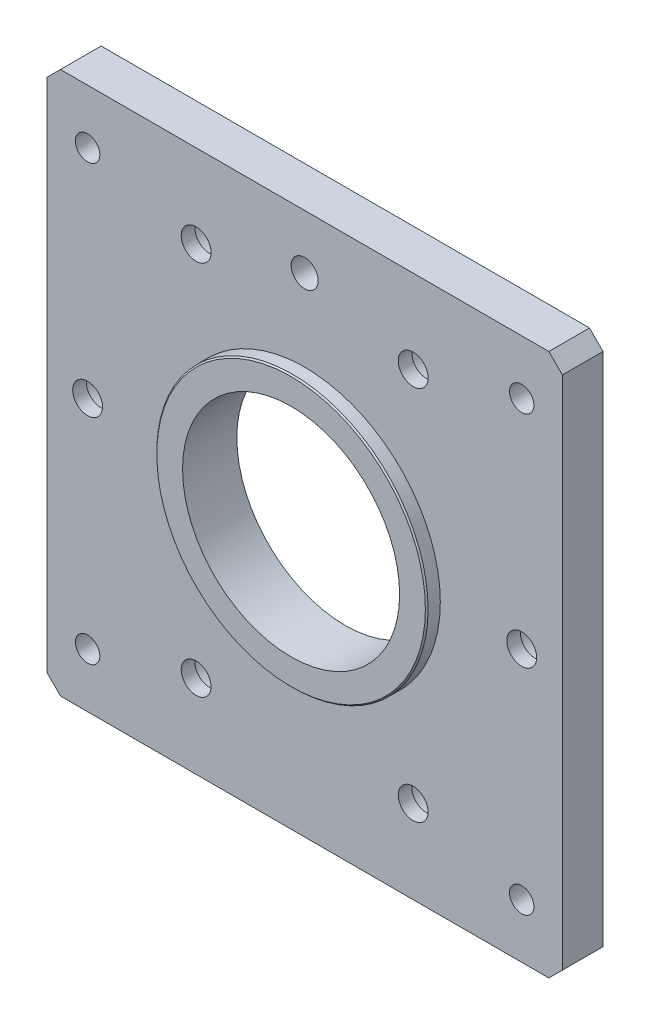
SolidWorks part; units mm, degrees
ref_plane "Alzado" through (0, 0, 0) normal (0, 0, 1) x (1, 0, 0)
ref_plane "Planta" through (0, 0, 0) normal (0, 1, 0) x (1, 0, 0)
ref_plane "Vista lateral" through (0, 0, 0) normal (1, 0, 0) x (0, 0, -1)
sketch "Croquis1" plane through (0, 0, 0) normal (0, 0, 1) x (1, 0, 0)
  line L1 (-95, 100) -> (95, 100)
  line L2 (-95, 100) -> (-95, -100)
  line L3 (-95, -100) -> (95, -100)
  line L4 (95, 100) -> (95, -100)
  line L5 (-95, 100) -> (95, -100) construction
  line L6 (-95, -100) -> (95, 100) construction
  circle A0 centre (0, 0) radius 80 construction
  circle A1 centre (80, 0) radius 5
  circle A2 centre (40, -69.282) radius 5
  circle A3 centre (-40, -69.282) radius 5
  circle A4 centre (-80, 0) radius 5
  circle A5 centre (-40, 69.282) radius 5
  circle A6 centre (40, 69.282) radius 5
  circle A7 centre (0, 80) radius 5
  circle A8 centre (0, 0) radius 40
  point P0 (0, 0)
  point P22 (0, 0)
  dimension "D1" = 160
  dimension "D4" = 10
  dimension "D6" = 10
  dimension "D7" = 80
  dimension "D2" = 190
  dimension "D3" = 200
  dimension "D5" = 6
extrude "Saliente-Extruir1" add sketch "Croquis1" along normal blind 20
sketch "Croquis2" plane through (0, 0, 20) normal (0, 0, 1) x (1, 0, 0)
  circle A0 centre (0, 0) radius 50
  dimension "D1" = 100
extrude "Cortar-Extruir1" cut sketch "Croquis2" against normal blind 5 flip side to cut
chamfer "Chaflán1" distance 0.5 angle 45 1 edges at (50, 0, 20)
chamfer "Chaflán2" distance 5 angle 45 4 edges at (95, -100, 7.5) (-95, -100, 7.5) (-95, 100, 7.5) (95, 100, 7.5)
sketch "Croquis3" plane through (0, 0, 15) normal (0, 0, 1) x (1, 0, 0)
  line L0 (-95, 95) -> (-95, -95) construction
  line L1 (-80, -80) -> (80, -80) construction
  line L2 (-80, -80) -> (-80, 80) construction
  line L3 (-80, 80) -> (80, 80) construction
  line L4 (80, -80) -> (80, 80) construction
  line L5 (-80, -80) -> (80, 80) construction
  line L6 (-80, 80) -> (80, -80) construction
  line L7 (90, 100) -> (-90, 100) construction
  circle A0 centre (-80, 80) radius 4.375
  circle A1 centre (80, 80) radius 4.375
  circle A2 centre (80, -80) radius 4.375
  circle A3 centre (-80, -80) radius 4.375
  point P0 (0, 0)
  dimension "D3" = 8.75
  dimension "D1" = 15
  dimension "D2" = 20
extrude "Cortar-Extruir2" cut sketch "Croquis3" against normal through all both and the other way through all
hole_wizard "Refrentado para tornillo tapón con cabeza de clavija de M101" positions "Croquis3D1" profile "Croquis4" counterbore size "M10" standard "Ansi Metric" end condition through all
sketch3d "Croquis3D1"
  line L1 (-40, 69.282, 15) -> (-40, 69.282, 0) construction
  line L2 (-80, 0, 15) -> (-80, 0, 0) construction
  line L3 (40, 69.282, 15) -> (40, 69.282, 0) construction
  line L4 (80, 0, 15) -> (80, 0, 0) construction
  line L5 (40, -69.282, 15) -> (40, -69.282, 0) construction
  line L6 (-40, -69.282, 15) -> (-40, -69.282, 0) construction
  point P0 (40, 69.282, 0)
  point P2 (80, 0, 0)
  point P4 (-80, 0, 0)
  point P6 (-40, -69.282, 0)
  point P8 (40, -69.282, 0)
  point P10 (-40, 69.282, 0)
  point P13 (0, 80, 0)
  point P16 (-40, 69.282, 0)
  point P19 (-80, 0, 0)
  point P22 (40, 69.282, 0)
  point P25 (80, 0, 0)
  point P28 (40, -69.282, 0)
  point P31 (-40, -69.282, 0)
sketch "Croquis4" plane through (40, 69.282, 0) normal (1, 0, 0) x (0, 1, 0)
  line L0 (0, 0) -> (0, 20)
  line L1 (0, 20) -> (5.5, 20)
  line L3 (5.5, 20) -> (5.5, 10)
  line L4 (5.5, 10) -> (9, 10)
  line L5 (9, 10) -> (9, 0)
  line L7 (9, 0) -> (0, 0)
  line L11 (0, -6.35) -> (0, 107.95) construction
  dimension "Diámetro de taladro hasta el siguiente" = 11
  dimension "Profundidad de taladro hasta el siguiente" = 20
  dimension "Diámetro de refrentado" = 18
  dimension "Profundidad de refrentado" = 10
hole_wizard "Taladro roscado M10x1.01" positions "Croquis5" profile "Croquis6" tap size "M10x1.0" standard "Ansi Metric" end condition through all
sketch "Croquis5" plane through (0, 0, 0) normal (0, 0, -1) x (-1, 0, 0)
  point P0 (-80, 80)
  point P3 (80, 80)
  point P6 (-80, -80)
  point P9 (80, -80)
sketch "Croquis6" plane through (80, 80, 0) normal (1, 0, 0) x (0, 1, 0)
  line L0 (0, 0) -> (0, 20)
  line L1 (0, 20) -> (4.5, 20)
  line L2 (4.5, 20) -> (4.5, 0)
  line L5 (4.5, 0) -> (0, 0)
  line L11 (0, -6.35) -> (0, 107.95) construction
  dimension "Diámetro de perforador para roscar hasta el siguiente" = 9
  dimension "Profundidad de perforador para roscar hasta el siguiente" = 20
cosmetic thread "Rosca de taladro1" parameters "D2"=10
cosmetic thread "Rosca de taladro2" parameters "D2"=10
cosmetic thread "Rosca de taladro3" parameters "D2"=10
cosmetic thread "Rosca de taladro4" parameters "D2"=10
